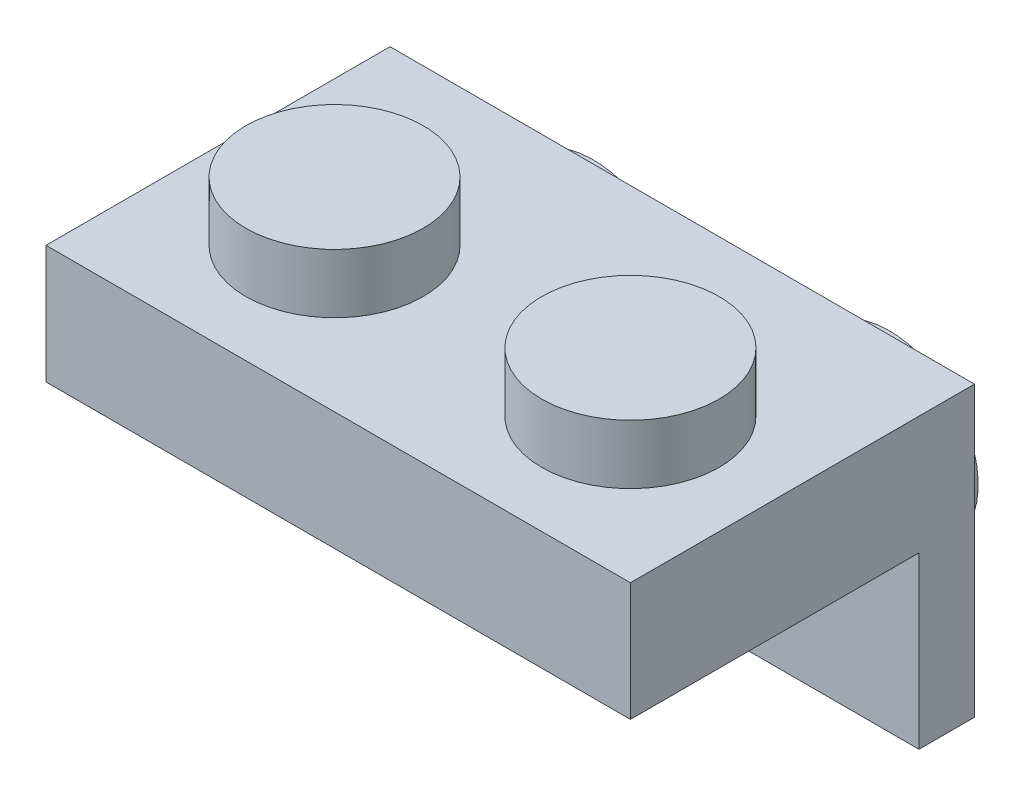
SolidWorks part; units mm, degrees
material "ABS"
ref_plane "Front Plane" through (0, 0, 0) normal (0, 0, 1) x (1, 0, 0)
ref_plane "Top Plane" through (0, 0, 0) normal (0, 1, 0) x (1, 0, 0)
ref_plane "Right Plane" through (0, 0, 0) normal (1, 0, 0) x (0, 0, -1)
sketch "Sketch1" plane through (0, 0, 0) normal (0, 0, 1) x (1, 0, 0)
  line L1 (0, 0) -> (15.8, 0)
  line L2 (0, 0) -> (0, 3.2)
  line L3 (0, 3.2) -> (15.8, 3.2)
  line L4 (15.8, 0) -> (15.8, 3.2)
  dimension "D1" = 3.2
  dimension "D2" = 15.8
extrude "Boss-Extrude1" add sketch "Sketch1" against normal blind 7.8
sketch "Sketch2" plane through (0, 3.2, 0) normal (0, 1, 0) x (1, 0, 0)
  line L0 (0, 7.8) -> (0, 0) construction
  line L1 (15.8, 0) -> (0, 0) construction
  circle A0 centre (3.9, 3.9) radius 2.4
  dimension "D1" = 4.8
  dimension "D2" = 3.9
  dimension "D3" = 3.9
extrude "Boss-Extrude2" add sketch "Sketch2" along normal blind 1.6 contours A0
pattern_linear "LPattern1" count 2 spacing 8 along (0, 0, 1) count 6 spacing 8 along (1, 0, 0) of "Boss-Extrude2"
shell "Shell1" thickness 1.2
sketch "Sketch3" plane through (0, 2, 0) normal (0, -1, 0) x (1, 0, 0)
  line L0 (0, 0) -> (15.8, 0) construction
  line L1 (15.8, -7.8) -> (15.8, 0) construction
  circle A0 centre (7.9, -3.9) radius 1.5
  circle A1 centre (7.9, -3.9) radius 0.6
  dimension "D1" = 3
  dimension "D2" = 1.2
  dimension "D3" = 3.9
  dimension "D4" = 7.9
extrude "Boss-Extrude3" add sketch "Sketch3" along normal offset from surface (1.8 mm away) 0.2 up to face at (7.9, 0, -3.9)
sketch "Sketch4" plane through (0, 0, -7.8) normal (0, 0, -1) x (-1, 0, 0)
  line L1 (-15.8, 3.2) -> (-15.8, -4.6)
  line L2 (-15.8, -4.6) -> (0, -4.6)
  line L3 (0, -4.6) -> (0, 3.2)
  line L5 (0, 3.2) -> (-15.8, 3.2)
  dimension "D3" = 7.8
extrude "Boss-Extrude4" add sketch "Sketch4" along normal blind 1.5
sketch "Sketch5" plane through (0, 0, -9.3) normal (0, 0, -1) x (-1, 0, 0)
  line L0 (0, -4.6) -> (0, 3.2) construction
  line L1 (-15.8, -4.6) -> (0, -4.6) construction
  circle A0 centre (-3.9, -0.7) radius 2.4
  circle A1 centre (-3.9, -0.7) radius 1.55
  dimension "D1" = 4.8
  dimension "D4" = 0.85
  dimension "D2" = 3.9
  dimension "D3" = 3.9
extrude "Boss-Extrude5" add sketch "Sketch5" along normal blind 1.6
pattern_linear "LPattern2" count 2 spacing 8 along (1, 0, 0) of "Boss-Extrude5"
